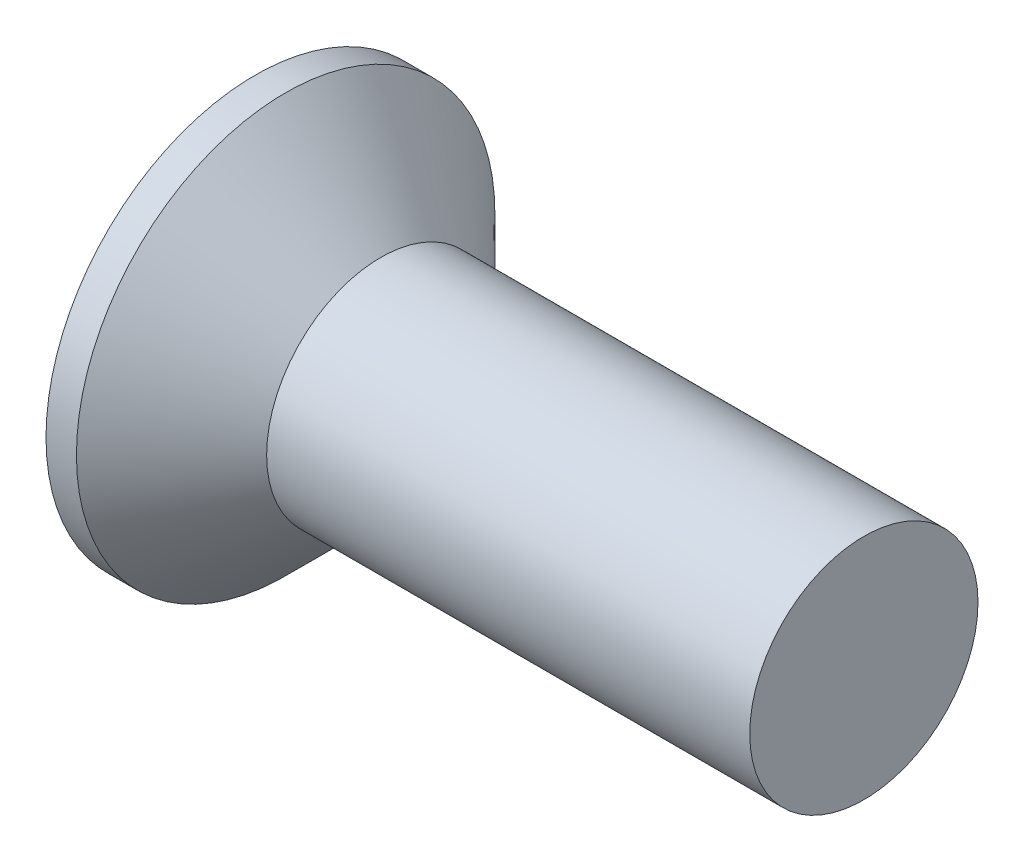
SolidWorks part; units mm, degrees
ref_plane "Plan de face" through (0, 0, 0) normal (0, 0, 1) x (1, 0, 0)
ref_plane "Plan de dessus" through (0, 0, 0) normal (0, 1, 0) x (1, 0, 0)
ref_plane "Plan de droite" through (0, 0, 0) normal (1, 0, 0) x (0, 0, -1)
sketch "Esquisse1" plane through (0, 0, 0) normal (0, 0, 1) x (1, 0, 0)
  line L0 (0, 0) -> (8, 0)
  line L1 (8, 0) -> (8, 1.5)
  line L2 (8, 1.5) -> (1.65, 1.5)
  line L4 (0, 2.75) -> (0, 0)
  line L5 (0, 2.75) -> (0.4, 2.75)
  line L6 (0.4, 2.75) -> (1.65, 1.5)
  dimension "D1" = 8
  dimension "D2" = 1.5
  dimension "D3" = 2.75
  dimension "D4" = 1.65
  dimension "D5" = 45
revolve "Révolution1" add sketch "Esquisse1" angle 360 about L0
equation "\"D3@Esquisse1\"=5.5/2"
